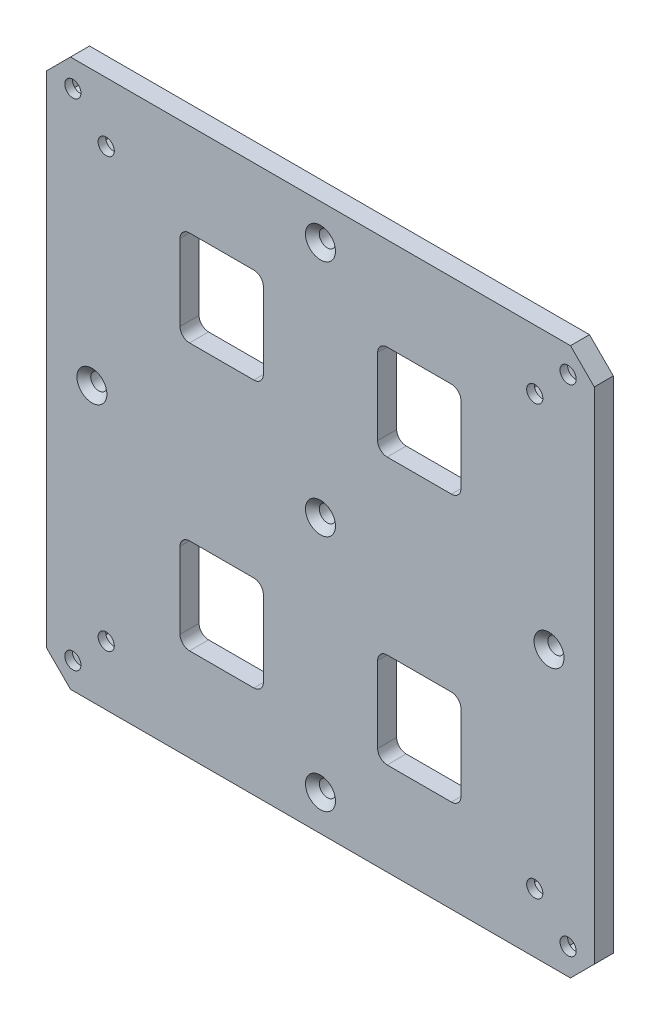
SolidWorks part; units mm, degrees
ref_plane "1" through (0, 0, 0) normal (0, 0, 1) x (1, 0, 0)
ref_plane "2" through (0, 0, 0) normal (0, 1, 0) x (1, 0, 0)
ref_plane "3" through (0, 0, 0) normal (1, 0, 0) x (0, 0, -1)
ref_plane "Front Plane" through (0, 0, 0) normal (0, -1, 0) x (1, 0, 0)
ref_plane "Right Plane" through (0, 0, 0) normal (1, 0, 0) x (0, 1, 0)
ref_plane "Top Plane" through (0, 0, 0) normal (0, 0, 1) x (1, 0, 0)
ref_plane "Plane1" through (0, 0, 1.6) normal (0, 0, 1) x (1, 0, 0)
sketch "Sketch1" plane through (0, 0, 0) normal (0, 0, 1) x (1, 0, 0)
  line L0 (-57.5, 57.5) -> (57.5, 57.5) construction
  line L1 (-57.5, 57.5) -> (-57.5, -57.5) construction
  line L2 (57.5, 57.5) -> (57.5, -57.5) construction
  line L3 (-57.5, -57.5) -> (57.5, -57.5) construction
  line L4 (0, 57.5) -> (0, 66.5129) construction
  line L5 (57.5, 0) -> (80.0122, 0) construction
  line L14 (-45, 45) -> (45, 45) construction
  line L15 (-45, 45) -> (-45, -45) construction
  line L16 (45, 45) -> (45, -45) construction
  line L17 (-45, -45) -> (45, -45) construction
  line L18 (0, 45) -> (0, 40.4761) construction
  line L19 (45, 0) -> (34.1739, 0) construction
  circle A0 centre (45, 45) radius 1.5 construction
  circle A1 centre (-45, 45) radius 1.5 construction
  circle A2 centre (-45, -45) radius 1.5 construction
  circle A3 centre (45, -45) radius 1.5 construction
  dimension "D4" = 3
  dimension "D1" = 115
  dimension "D2" = 115
  dimension "D3" = 90
  dimension "D5" = 90
sketch "Sketch2" plane through (0, 0, 0) normal (0, 0, 1) x (1, 0, 0)
  line L8 (0, 57.5) -> (0, 0)
  line L9 (0, 0) -> (57.5, 0)
  line L10 (57.5, 0) -> (57.5, 57.5)
  line L14 (57.5, 57.5) -> (0, 57.5)
  line L15 (-57.5, 57.5) -> (57.5, 57.5) construction
  line L16 (57.5, 57.5) -> (57.5, -57.5) construction
extrude "Boss-Extrude1" add sketch "Sketch2" along normal blind 4
sketch "Sketch12" plane through (0, 0, 0) normal (0, 0, 1) x (1, 0, 0)
  line L1 (45, 41.7668) -> (47.8, 43.3834)
  line L2 (47.8, 43.3834) -> (47.8, 46.6166)
  line L3 (47.8, 46.6166) -> (45, 48.2332)
  line L4 (45, 48.2332) -> (42.2, 46.6166)
  line L5 (42.2, 46.6166) -> (42.2, 43.3834)
  line L6 (42.2, 43.3834) -> (45, 41.7668)
  circle A0 centre (45, 45) radius 2.8 construction
  circle A1 centre (45, 45) radius 1.5 construction
  dimension "D1" = 5.6
extrude "Cut-Extrude4" cut sketch "Sketch12" along normal blind 2.4
hole_wizard "M3 Clearance Hole1" positions "Sketch3" profile "Sketch5" hole size "M3" standard "ANSI Metric" end condition through all
sketch "Sketch3" plane through (0, 0, 4) normal (0, 0, 1) x (1, 0, 0)
  circle A0 centre (45, 45) radius 1.5 construction
  circle A1 centre (-45, 45) radius 1.5 construction
  circle A2 centre (-45, -45) radius 1.5 construction
  circle A3 centre (45, -45) radius 1.5 construction
  point P0 (45, 45)
  point P2 (-45, 45)
  point P4 (-45, -45)
  point P6 (45, -45)
sketch "Sketch5" plane through (45, 45, 4) normal (1, 0, 0) x (0, -1, 0)
  line L0 (0, 0) -> (0, 4)
  line L1 (0, 4) -> (1.7, 4)
  line L2 (1.7, 4) -> (1.7, 0)
  line L5 (1.7, 0) -> (0, 0)
  line L11 (0, -6.35) -> (0, 107.95) construction
  dimension "Thru Hole Dia." = 3.4
  dimension "Thru Hole Depth" = 4
sketch "Sketch6" plane through (0, 0, 0) normal (0, 0, 1) x (1, 0, 0)
  line L0 (0, 50) -> (0, 0) construction
  line L1 (0, 0) -> (48, 0) construction
  circle A3 centre (0, 50) radius 1.5
  circle A4 centre (0, 0) radius 1.5
  circle A5 centre (48, 0) radius 1.5
  dimension "D1" = 3
  dimension "D2" = 50
  dimension "D3" = 48
hole_wizard "CSK for M3 Flat Head Machine Screw1" positions "Sketch9" profile "Sketch10" countersink size "M3" standard "ANSI Metric" end condition through all
sketch "Sketch9" plane through (0, 0, 4) normal (0, 0, 1) x (1, 0, 0)
  circle A3 centre (0, 50) radius 1.5 construction
  circle A4 centre (0, 0) radius 1.5 construction
  circle A5 centre (48, 0) radius 1.5 construction
  point P0 (0, 50)
  point P2 (0, 0)
  point P4 (48, 0)
sketch "Sketch10" plane through (0, 50, 4) normal (1, 0, 0) x (0, -1, 0)
  line L0 (0, 0) -> (0, 4)
  line L1 (0, 4) -> (1.7, 4)
  line L2 (1.7, 4) -> (1.7, 1.45)
  line L3 (1.7, 1.45) -> (3.15, 0)
  line L5 (3.15, 0) -> (0, 0)
  line L6 (-1.7, 1.45) -> (-3.15, 0) construction
  line L11 (0, -6.35) -> (0, 107.95) construction
  dimension "Thru Hole Dia." = 3.4
  dimension "Thru Hole Depth" = 4
  dimension "Near C'Sink Dia." = 6.3
  dimension "Near C'Sink Angle" = 90
sketch "Sketch11" plane through (0, 0, 0) normal (0, 0, 1) x (1, 0, 0)
  line L0 (12, 38) -> (12, 18)
  line L1 (12, 38) -> (29.5, 38)
  line L2 (12, 18) -> (29.5, 18)
  line L3 (29.5, 38) -> (29.5, 18)
  line L4 (12, 28) -> (8.7244, 28) construction
  line L5 (0, -31.3359) -> (0, 31.3359) construction
  dimension "D1" = 28
  dimension "D2" = 20
  dimension "D3" = 12
  dimension "D4" = 29.5
extrude "Cut-Extrude3" cut sketch "Sketch11" along normal through all
fillet "Fillet1" radius 2 4 edges at (12, 18, 2) (29.5, 18, 2) (29.5, 38, 2) (12, 38, 2)
sketch "Sketch15" plane through (0, 0, 0) normal (0, 0, 1) x (1, 0, 0)
  line L0 (0, 52) -> (40, 52) construction
  line L3 (52, 40) -> (52, 0) construction
  line L4 (52, 0) -> (0, 0) construction
  line L5 (0, 0) -> (0, 52) construction
  line L7 (54.2862, 49.7138) -> (55.123, 52.8368)
  line L8 (55.123, 52.8368) -> (52.8368, 55.123)
  line L9 (52.8368, 55.123) -> (49.7138, 54.2862)
  line L10 (49.7138, 54.2862) -> (48.877, 51.1632)
  line L11 (48.877, 51.1632) -> (51.1632, 48.877)
  line L12 (51.1632, 48.877) -> (54.2862, 49.7138)
  circle A3 centre (52, 52) radius 2.8 construction
  point P2 (0, 0)
  point P3 (50.1143, 52)
  point P9 (54.5953, 50.0719)
  dimension "D4" = 135
  dimension "D3" = 5.6
  dimension "D1" = 52
  dimension "D2" = 52
extrude "Cut-Extrude6" cut sketch "Sketch15" along normal blind 2.4 from surface at 0 starting at face at (45, 45, 0)
hole_wizard "M3 Clearance Hole2" positions "Sketch13" profile "Sketch14" hole size "M3" standard "ANSI Metric" end condition through all
sketch "Sketch13" plane through (0, 0, 0) normal (0, 0, -1) x (-1, 0, 0)
  circle A2 centre (-52, 52) radius 2.8 construction
  point P0 (-52, 52)
  point P13 (0, 0)
sketch "Sketch14" plane through (52, 52, 0) normal (1, 0, 0) x (0, 1, 0)
  line L0 (0, 0) -> (0, 4)
  line L1 (0, 4) -> (1.7, 4)
  line L2 (1.7, 4) -> (1.7, 0)
  line L5 (1.7, 0) -> (0, 0)
  line L11 (0, -6.35) -> (0, 107.95) construction
  dimension "Thru Hole Dia." = 3.4
  dimension "Thru Hole Depth" = 4
chamfer "Chamfer1" distance 5 angle 45 1 edges at (57.5, 57.5, 2)
mirror "Mirror1" about plane through (0, 0, 0) normal (0, -1, 0) of bodies 110 102
mirror "Mirror2" about plane through (0, 0, 0) normal (1, 0, 0) of bodies 103
